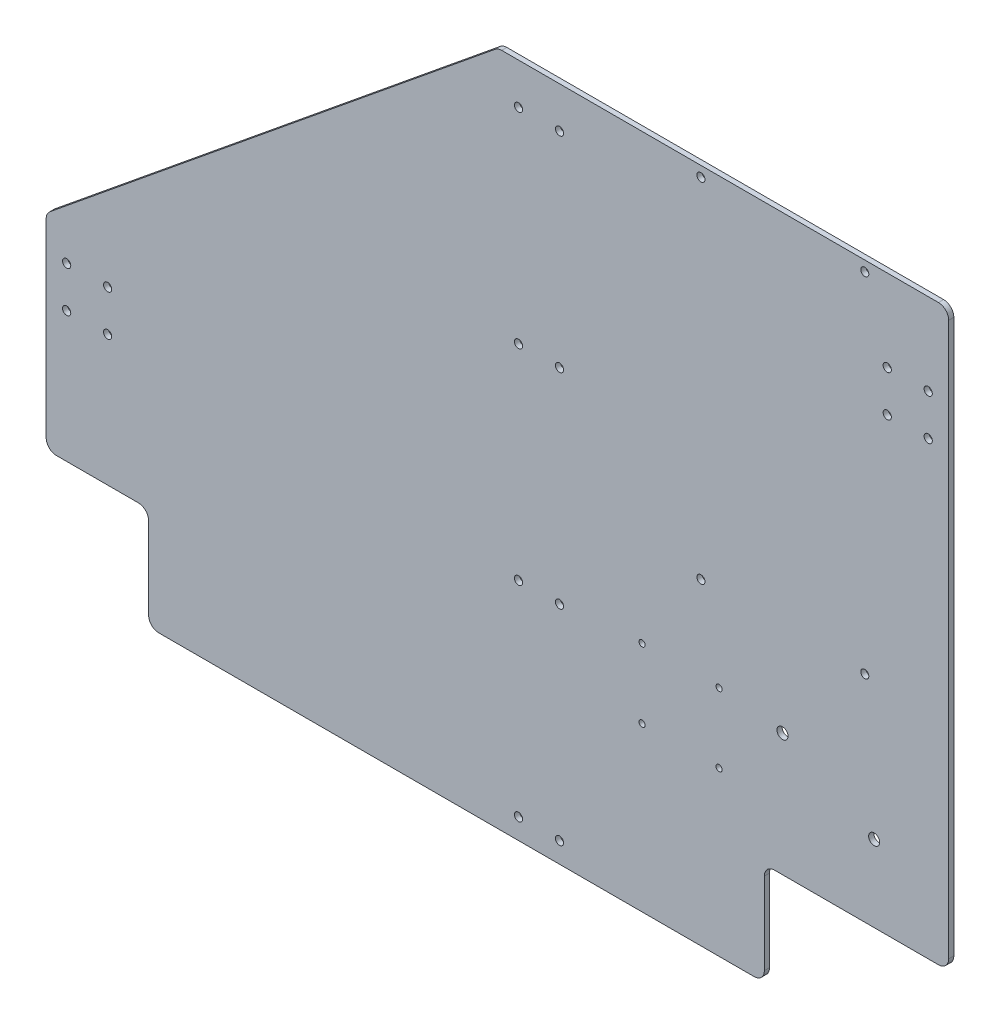
SolidWorks part; units mm, degrees
ref_plane "Front Plane" through (0, 0, 0) normal (0, 0, 1) x (1, 0, 0)
ref_plane "Top Plane" through (0, 0, 0) normal (0, 1, 0) x (1, 0, 0)
ref_plane "Right Plane" through (0, 0, 0) normal (1, 0, 0) x (0, 0, -1)
sketch "Sketch1" plane through (0, 0, 0) normal (0, 0, 1) x (1, 0, 0)
  line L1 (0, 0) -> (508.762, 0) construction
  line L2 (0, 0) -> (0, 419.1) construction
  line L3 (0, 419.1) -> (508.762, 419.1) construction
  line L4 (508.762, 0) -> (508.762, 419.1) construction
  line L5 (280.162, 0) -> (330.962, 0) construction
  line L6 (280.162, 0) -> (280.162, 419.1) construction
  line L7 (280.162, 419.1) -> (330.962, 419.1) construction
  line L8 (330.962, 0) -> (330.962, 419.1) construction
  line L9 (0, 0) -> (63.5, 0) construction
  line L10 (0, 0) -> (0, 63.5) construction
  line L11 (0, 63.5) -> (63.5, 63.5)
  line L12 (63.5, 0) -> (63.5, 63.5)
  line L13 (508.762, 0) -> (445.262, 0) construction
  line L14 (508.762, 0) -> (508.762, 63.5) construction
  line L15 (508.762, 63.5) -> (445.262, 63.5)
  line L16 (445.262, 0) -> (445.262, 63.5)
  line L17 (292.862, 12.7) -> (318.262, 12.7) construction
  line L18 (292.862, 12.7) -> (292.862, 139.7) construction
  line L19 (508.762, 63.5) -> (508.762, 419.1)
  line L20 (508.762, 419.1) -> (280.162, 419.1)
  line L21 (63.5, 0) -> (445.262, 0)
  line L22 (0, 63.5) -> (0, 190.5)
  line L23 (0, 190.5) -> (280.162, 419.1)
  line L24 (508.762, 419.1) -> (559.562, 419.1)
  line L25 (330.962, 381) -> (508.762, 381) construction
  line L26 (330.962, 381) -> (330.962, 330.2) construction
  line L27 (330.962, 330.2) -> (508.762, 330.2) construction
  line L28 (508.762, 381) -> (508.762, 330.2) construction
  line L29 (521.462, 368.3) -> (546.862, 368.3) construction
  line L30 (521.462, 368.3) -> (521.462, 342.9) construction
  line L31 (521.462, 342.9) -> (546.862, 342.9) construction
  line L32 (546.862, 368.3) -> (546.862, 342.9) construction
  line L33 (521.462, 368.3) -> (546.862, 342.9) construction
  line L34 (521.462, 342.9) -> (546.862, 368.3) construction
  line L35 (0, 0) -> (50.8, 0) construction
  line L36 (0, 0) -> (0, 182.5625) construction
  line L37 (0, 182.5625) -> (50.8, 182.5625) construction
  line L38 (50.8, 0) -> (50.8, 182.5625) construction
  line L39 (12.7, 169.8625) -> (38.1, 169.8625) construction
  line L40 (12.7, 169.8625) -> (12.7, 144.4625) construction
  line L41 (12.7, 144.4625) -> (38.1, 144.4625) construction
  line L42 (38.1, 169.8625) -> (38.1, 144.4625) construction
  line L43 (12.7, 169.8625) -> (38.1, 144.4625) construction
  line L44 (12.7, 144.4625) -> (38.1, 169.8625) construction
  line L45 (559.562, 419.1) -> (559.562, 63.5)
  line L46 (559.562, 63.5) -> (508.762, 63.5)
  circle A0 centre (318.262, 12.7) radius 2.54
  circle A1 centre (292.862, 12.7) radius 2.54
  circle A2 centre (292.862, 139.7) radius 2.54
  circle A3 centre (318.262, 139.7) radius 2.54
  circle A4 centre (292.862, 266.7) radius 2.54
  circle A5 centre (318.262, 266.7) radius 2.54
  circle A6 centre (292.862, 393.7) radius 2.54
  circle A7 centre (318.262, 393.7) radius 2.54
  circle A8 centre (521.462, 368.3) radius 2.54
  circle A9 centre (546.862, 368.3) radius 2.54
  circle A10 centre (546.862, 342.9) radius 2.54
  circle A11 centre (521.462, 342.9) radius 2.54
  circle A12 centre (12.7, 169.8625) radius 2.54
  circle A13 centre (38.1, 169.8625) radius 2.54
  circle A14 centre (38.1, 144.4625) radius 2.54
  circle A15 centre (12.7, 144.4625) radius 2.54
  point P41 (534.162, 355.6)
  point P53 (25.4, 157.1625)
  point P55 (25.4, 182.5625)
  dimension "D9" = 5.08
  dimension "D19" = 5.08
  dimension "D24" = 5.08
  dimension "20.03" = 508.762
  dimension "D2" = 419.1
  dimension "D3" = 50.8
  dimension "D4" = 177.8
  dimension "D5" = 63.5
  dimension "D6" = 63.5
  dimension "D7" = 25.4
  dimension "D8" = 12.7
  dimension "D10" = 12.7
  dimension "D12" = 127
  dimension "D13" = 127
  dimension "D14" = 50.8
  dimension "D15" = 38.1
  dimension "D16" = 12.7
  dimension "D17" = 12.7
  dimension "D18" = 25.4
  dimension "D20" = 182.5625
  dimension "D21" = 50.8
  dimension "D22" = 25.4
  dimension "D23" = 25.4
  dimension "D25" = 50.8
  dimension "D11" = 4
extrude "Boss-Extrude1" add sketch "Sketch1" along normal blind 3.175 contours L1 L16 L15 L4 L3 L2 L11 L12 | L46 L45 L24 L19
fillet "Fillet1" radius 6.35 9 edges at (280.162, 419.1, 1.5875) (445.262, 63.5, 1.5875) (445.262, 0, 1.5875) (63.5, 0, 1.5875) (63.5, 63.5, 1.5875) (0, 63.5, 1.5875) (0, 190.5, 1.5875) (559.562, 419.1, 1.5875) (559.562, 63.5, 1.5875)
sketch "Sketch2" plane through (0, 0, 3.175) normal (0, 0, 1) x (1, 0, 0)
  line L9 (167.64, 210.82) -> (167.64, 160.02) construction
  line L10 (116.84, 210.82) -> (116.84, 160.02) construction
  line L11 (66.04, 210.82) -> (66.04, 160.02) construction
  line L12 (0, 69.85) -> (0, 187.4857) construction
  line L13 (6.35, 63.5) -> (57.15, 63.5) construction
  circle A9 centre (66.04, 210.82) radius 2.54
  circle A10 centre (116.84, 210.82) radius 2.54
  circle A11 centre (167.64, 210.82) radius 2.54
  circle A12 centre (167.64, 160.02) radius 2.54
  circle A13 centre (116.84, 160.02) radius 2.54
  circle A14 centre (66.04, 160.02) radius 2.54
  dimension "D9" = 5.08
  dimension "D7" = 50.8
  dimension "D8" = 50.8
  dimension "D10" = 50.8
  dimension "D11" = 66.04
  dimension "D12" = 147.32
sketch "Sketch3" [suppressed] plane through (0, 0, 3.175) normal (0, 0, 1) x (1, 0, 0)
  line L1 (419.862, 228.6) -> (521.462, 228.6) construction
  line L2 (419.862, 228.6) -> (419.862, 101.6) construction
  line L3 (419.862, 101.6) -> (521.462, 101.6) construction
  line L4 (521.462, 228.6) -> (521.462, 101.6) construction
  line L5 (553.212, 63.5) -> (451.612, 63.5) construction
  line L7 (559.562, 412.75) -> (559.562, 69.85) construction
  circle A0 centre (521.462, 228.6) radius 1.4224
  circle A1 centre (419.862, 228.6) radius 1.4224
  circle A2 centre (419.862, 101.6) radius 1.4224
  circle A3 centre (521.462, 101.6) radius 1.4224
  dimension "D3" = 2.8448
  dimension "D1" = 101.6
  dimension "D2" = 127
  dimension "D4" = 38.1
  dimension "D5" = 38.1
extrude "Cut-Extrude3" [suppressed] cut sketch "Sketch3" against normal through all
sketch "Sketch4" [suppressed] plane through (0, 0, 3.175) normal (0, 0, 1) x (1, 0, 0)
  circle A0 centre (471.363, 392.8278) radius 19.113
extrude "Cut-Extrude4" [suppressed] cut sketch "Sketch4" against normal blind 1320.8
sketch "Sketch5" [suppressed] plane through (0, 0, 3.175) normal (0, 0, 1) x (1, 0, 0)
  line L1 (553.212, 419.1) -> (282.4239, 419.1) construction
  line L2 (559.562, 412.75) -> (559.562, 69.85) construction
  circle A0 centre (520.7, 398.145) radius 2.54
  circle A1 centre (497.84, 398.145) radius 2.54
  dimension "D2" = 5.08
  dimension "D1" = 38.862
  dimension "D3" = 22.86
  dimension "D4" = 20.955
extrude "Cut-Extrude5" [suppressed] cut sketch "Sketch5" against normal through all
sketch "Sketch6" plane through (0, 0, 0) normal (0, 0, -1) x (-1, 0, 0)
  circle A0 centre (-507.5341, 412.7222) radius 2.5
  circle A1 centre (-405.9341, 412.7222) radius 2.5
  circle A2 centre (-507.5341, 196.8222) radius 2.5
  circle A3 centre (-513.3621, 110.9575) radius 3.429
  circle A4 centre (-456.5246, 139.5278) radius 3.429
  arc A5 (-513.4, 114.3863) -> (-513.3242, 107.5287) centre (-513.3621, 110.9575) ccw construction
  arc A6 (-513.3242, 107.5287) -> (-513.4, 114.3863) centre (-513.3621, 110.9575) ccw construction
  circle A7 centre (-405.9341, 196.8222) radius 2.5
  circle A8 centre (-507.5341, 412.7222) radius 2.5 construction
  circle A9 centre (-417.195, 144.1893) radius 1.905
  circle A10 centre (-369.443, 144.1893) radius 1.905
  circle A11 centre (-417.1927, 101.1363) radius 1.905
  circle A12 centre (-369.443, 101.1363) radius 1.905
  circle A13 centre (-369.443, 101.1363) radius 1.905 construction
extrude "Cut-Extrude6" cut sketch "Sketch6" against normal blind 5.08
sketch "Sketch7" plane through (0, 0, 3.175) normal (0, 0, 1) x (1, 0, 0)
  line L0 (-790.0298, 431.8) -> (49209.9702, 431.8) construction
  line L1 (-801.1932, -12.7) -> (49198.8068, -12.7) construction
  line L2 (-12.7, -863.7899) -> (-12.7, 49136.2101) construction
  line L3 (553.212, 419.1) -> (282.4239, 419.1) construction
  line L4 (69.85, 0) -> (438.912, 0) construction
  line L5 (0, 69.85) -> (0, 187.4857) construction
  circle A0 centre (217.8163, 349.4332) radius 7.8831
  circle A1 centre (92.1419, 247.7673) radius 10.4027
  circle A2 centre (84.2996, 22.3214) radius 12.7268
  circle A3 centre (422.3873, 22.3214) radius 7.0873
  circle A4 centre (461.1633, 408.5522) radius 6.2126
  point P5 (-12.7, 431.8)
  point P7 (-12.7, -12.7)
  point P18 (461.1633, 408.5522)
  dimension "D1" = 12.7
  dimension "D2" = 12.7
  dimension "D3" = 12.7
